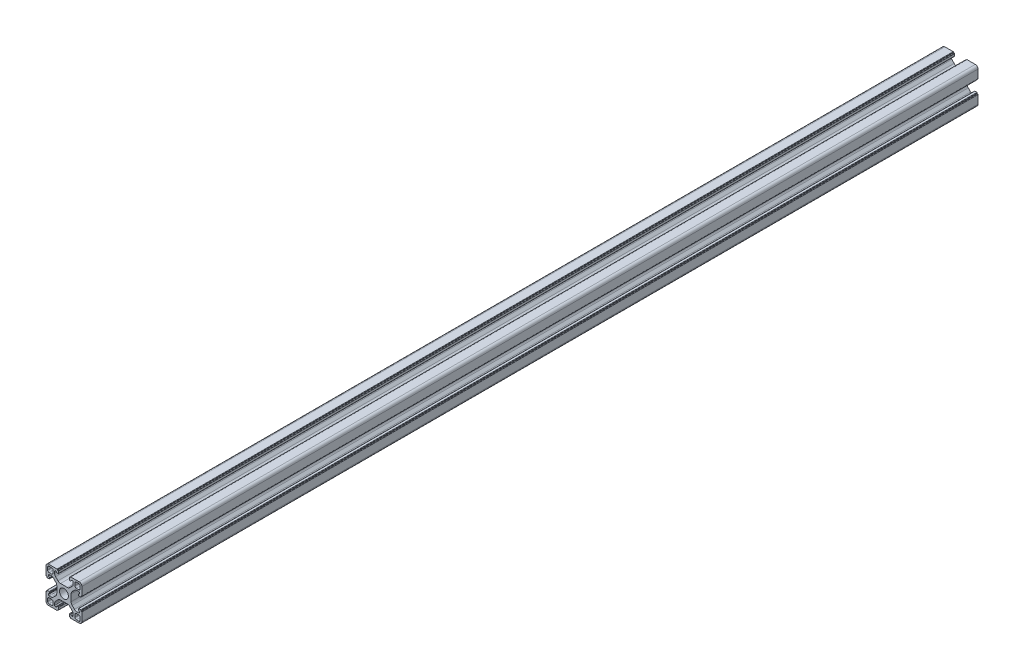
SolidWorks part; units mm, degrees
material "1060 Сплав"
ref_plane "Спереди" through (0, 0, 0) normal (0, 0, 1) x (1, 0, 0)
ref_plane "Сверху" through (0, 0, 0) normal (0, 1, 0) x (1, 0, 0)
ref_plane "Справа" through (0, 0, 0) normal (1, 0, 0) x (0, 0, -1)
sketch "Эскиз1" plane through (0, 0, 0) normal (0, 0, 1) x (1, 0, 0)
  line L0 (-22.0052, 70.3096) -> (-25.0052, 67.3096) construction
  line L1 (-31.1052, 65.2096) -> (-29.2064, 65.2096)
  line L2 (-31.1052, 61.2096) -> (-21.1052, 71.2096) construction
  line L3 (-23.5052, 68.8096) -> (-25.0052, 70.3096) construction
  line L4 (-27.7922, 65.7954) -> (-26.4909, 67.0967)
  line L5 (-24.2052, 67.3096) -> (-22.8052, 67.3096)
  line L6 (-25.0052, 68.1096) -> (-25.0052, 69.5096)
  line L7 (-22.8052, 70.3096) -> (-24.2052, 70.3096)
  line L8 (-25.9052, 69.4096) -> (-25.9052, 68.5109)
  line L9 (-27.3419, 69.2829) -> (-26.8616, 69.7632)
  line L10 (-27.9052, 70.7587) -> (-27.4052, 70.7587)
  line L11 (-27.5187, 69.2096) -> (-27.8052, 69.2096)
  line L12 (-26.508, 69.9096) -> (-26.4052, 69.9096)
  line L13 (-27.4052, 71.0596) -> (-27.4052, 70.7587)
  line L14 (-28.0552, 70.6087) -> (-28.0552, 69.4596)
  line L15 (-22.6052, 71.2096) -> (-27.2552, 71.2096)
  line L16 (-22.0052, 69.5096) -> (-22.0052, 68.1096)
  line L17 (-21.1052, 69.7096) -> (-21.1052, 65.0596)
  line L18 (-21.7061, 64.2596) -> (-22.8552, 64.2596)
  line L19 (-21.2552, 64.9096) -> (-21.5561, 64.9096)
  line L20 (-22.4052, 65.8068) -> (-22.4052, 65.9096)
  line L21 (-23.1052, 64.7961) -> (-23.1052, 64.5096)
  line L22 (-21.5561, 64.4096) -> (-21.5561, 64.9096)
  line L23 (-23.0319, 64.9729) -> (-22.5516, 65.4532)
  line L24 (-22.9052, 66.4096) -> (-23.8039, 66.4096)
  line L25 (-26.5194, 64.5226) -> (-25.2181, 65.8239)
  line L26 (-27.1052, 61.2096) -> (-27.1052, 63.1084)
  line L27 (-27.1052, 61.2096) -> (-27.1052, 59.3109)
  line L28 (-26.5194, 57.8967) -> (-25.2181, 56.5954)
  line L29 (-25.0052, 54.3096) -> (-25.0052, 52.9096)
  line L30 (-24.2052, 55.1096) -> (-22.8052, 55.1096)
  line L31 (-22.0052, 52.9096) -> (-22.0052, 54.3096)
  line L32 (-22.9052, 56.0096) -> (-23.8039, 56.0096)
  line L33 (-23.0319, 57.4464) -> (-22.5516, 56.9661)
  line L34 (-21.5561, 58.0096) -> (-21.5561, 57.5096)
  line L35 (-23.1052, 57.6232) -> (-23.1052, 57.9096)
  line L36 (-22.4052, 56.6125) -> (-22.4052, 56.5096)
  line L37 (-21.2552, 57.5096) -> (-21.5561, 57.5096)
  line L38 (-21.7061, 58.1596) -> (-22.8552, 58.1596)
  line L39 (-21.1052, 52.7096) -> (-21.1052, 57.3596)
  line L40 (-22.8052, 52.1096) -> (-24.2052, 52.1096)
  line L41 (-22.6052, 51.2096) -> (-27.2552, 51.2096)
  line L42 (-28.0552, 51.8106) -> (-28.0552, 52.9596)
  line L43 (-27.4052, 51.3596) -> (-27.4052, 51.6606)
  line L44 (-26.508, 52.5096) -> (-26.4052, 52.5096)
  line L45 (-27.5187, 53.2096) -> (-27.8052, 53.2096)
  line L46 (-27.9052, 51.6606) -> (-27.4052, 51.6606)
  line L47 (-27.3419, 53.1364) -> (-26.8616, 52.6561)
  line L48 (-25.9052, 53.0096) -> (-25.9052, 53.9084)
  line L49 (-27.7922, 56.6239) -> (-26.4909, 55.3226)
  line L50 (-31.1052, 57.2096) -> (-29.2064, 57.2096)
  line L51 (-22.0052, 52.1096) -> (-25.0052, 55.1096) construction
  line L52 (-31.1052, 61.2096) -> (-21.1052, 51.2096) construction
  line L53 (-23.5052, 53.6096) -> (-22.0052, 55.1096) construction
  line L54 (-31.1052, 57.2096) -> (-33.0039, 57.2096)
  line L55 (-34.4181, 56.6239) -> (-35.7194, 55.3226)
  line L56 (-38.0052, 55.1096) -> (-39.4052, 55.1096)
  line L57 (-37.2052, 54.3096) -> (-37.2052, 52.9096)
  line L58 (-39.4052, 52.1096) -> (-38.0052, 52.1096)
  line L59 (-36.3052, 53.0096) -> (-36.3052, 53.9084)
  line L60 (-34.8684, 53.1364) -> (-35.3487, 52.6561)
  line L61 (-34.3052, 51.6606) -> (-34.8052, 51.6606)
  line L62 (-34.6916, 53.2096) -> (-34.4052, 53.2096)
  line L63 (-35.7023, 52.5096) -> (-35.8052, 52.5096)
  line L64 (-34.8052, 51.3596) -> (-34.8052, 51.6606)
  line L65 (-34.1552, 51.8106) -> (-34.1552, 52.9596)
  line L66 (-39.6052, 51.2096) -> (-34.9552, 51.2096)
  line L67 (-40.2052, 52.9096) -> (-40.2052, 54.3096)
  line L68 (-41.1052, 52.7096) -> (-41.1052, 57.3596)
  line L69 (-40.5042, 58.1596) -> (-39.3552, 58.1596)
  line L70 (-40.9552, 57.5096) -> (-40.6542, 57.5096)
  line L71 (-39.8052, 56.6125) -> (-39.8052, 56.5096)
  line L72 (-39.1052, 57.6232) -> (-39.1052, 57.9096)
  line L73 (-40.6542, 58.0096) -> (-40.6542, 57.5096)
  line L74 (-39.1784, 57.4464) -> (-39.6587, 56.9661)
  line L75 (-39.3052, 56.0096) -> (-38.4064, 56.0096)
  line L76 (-35.6909, 57.8967) -> (-36.9922, 56.5954)
  line L77 (-35.1052, 61.2096) -> (-35.1052, 59.3109)
  line L78 (-40.2052, 52.1096) -> (-37.2052, 55.1096) construction
  line L79 (-31.1052, 61.2096) -> (-41.1052, 51.2096) construction
  line L80 (-38.7052, 53.6096) -> (-37.2052, 52.1096) construction
  line L81 (-35.1052, 61.2096) -> (-35.1052, 63.1084)
  line L82 (-35.6909, 64.5226) -> (-36.9922, 65.8239)
  line L83 (-37.2052, 68.1096) -> (-37.2052, 69.5096)
  line L84 (-38.0052, 67.3096) -> (-39.4052, 67.3096)
  line L85 (-40.2052, 69.5096) -> (-40.2052, 68.1096)
  line L86 (-39.3052, 66.4096) -> (-38.4064, 66.4096)
  line L87 (-39.1784, 64.9729) -> (-39.6587, 65.4532)
  line L88 (-40.6542, 64.4096) -> (-40.6542, 64.9096)
  line L89 (-39.1052, 64.7961) -> (-39.1052, 64.5096)
  line L90 (-39.8052, 65.8068) -> (-39.8052, 65.9096)
  line L91 (-40.9552, 64.9096) -> (-40.6542, 64.9096)
  line L92 (-40.5042, 64.2596) -> (-39.3552, 64.2596)
  line L93 (-41.1052, 69.7096) -> (-41.1052, 65.0596)
  line L94 (-39.4052, 70.3096) -> (-38.0052, 70.3096)
  line L95 (-39.6052, 71.2096) -> (-34.9552, 71.2096)
  line L96 (-34.1552, 70.6087) -> (-34.1552, 69.4596)
  line L97 (-34.8052, 71.0596) -> (-34.8052, 70.7587)
  line L98 (-35.7023, 69.9096) -> (-35.8052, 69.9096)
  line L99 (-34.6916, 69.2096) -> (-34.4052, 69.2096)
  line L100 (-34.3052, 70.7587) -> (-34.8052, 70.7587)
  line L101 (-34.8684, 69.2829) -> (-35.3487, 69.7632)
  line L102 (-36.3052, 69.4096) -> (-36.3052, 68.5109)
  line L103 (-34.4181, 65.7954) -> (-35.7194, 67.0967)
  line L104 (-31.1052, 65.2096) -> (-33.0039, 65.2096)
  line L105 (-42.8692, 61.2096) -> (-19.6008, 61.2096) construction
  line L106 (-40.2052, 70.3096) -> (-37.2052, 67.3096) construction
  line L107 (-31.1052, 49.1232) -> (-31.1052, 71.9286) construction
  line L108 (-31.1052, 61.2096) -> (-41.1052, 71.2096) construction
  line L109 (-38.7052, 68.8096) -> (-40.2052, 67.3096) construction
  arc A0 (-22.0052, 69.5096) -> (-22.8052, 70.3096) centre (-22.8052, 69.5096) ccw
  arc A1 (-24.2052, 70.3096) -> (-25.0052, 69.5096) centre (-24.2052, 69.5096) ccw
  arc A2 (-24.2052, 67.3096) -> (-25.0052, 68.1096) centre (-24.2052, 68.1096) cw
  arc A3 (-22.6052, 71.2096) -> (-21.1052, 69.7096) centre (-22.6052, 69.7096) cw
  arc A4 (-27.9052, 70.7587) -> (-28.0552, 70.6087) centre (-27.9052, 70.6087) ccw
  arc A5 (-27.2552, 71.2096) -> (-27.4052, 71.0596) centre (-27.2552, 71.0596) ccw
  arc A6 (-27.5187, 69.2096) -> (-27.3419, 69.2829) centre (-27.5187, 69.4596) ccw
  arc A7 (-27.8052, 69.2096) -> (-28.0552, 69.4596) centre (-27.8052, 69.4596) cw
  arc A8 (-26.8616, 69.7632) -> (-26.508, 69.9096) centre (-26.508, 69.4096) cw
  arc A9 (-26.4052, 69.9096) -> (-25.9052, 69.4096) centre (-26.4052, 69.4096) cw
  arc A10 (-28.6052, 61.2096) -> (-31.1052, 63.7096) centre (-31.1052, 61.2096) ccw
  arc A11 (-29.2064, 65.2096) -> (-27.7922, 65.7954) centre (-29.2064, 67.2096) ccw
  arc A12 (-25.9052, 68.5109) -> (-26.4909, 67.0967) centre (-27.9052, 68.5109) cw
  arc A13 (-22.0052, 68.1096) -> (-22.8052, 67.3096) centre (-22.8052, 68.1096) cw
  arc A14 (-22.4052, 65.9096) -> (-22.9052, 66.4096) centre (-22.9052, 65.9096) ccw
  arc A15 (-22.5516, 65.4532) -> (-22.4052, 65.8068) centre (-22.9052, 65.8068) ccw
  arc A16 (-23.1052, 64.5096) -> (-22.8552, 64.2596) centre (-22.8552, 64.5096) ccw
  arc A17 (-23.1052, 64.7961) -> (-23.0319, 64.9729) centre (-22.8552, 64.7961) cw
  arc A18 (-21.1052, 65.0596) -> (-21.2552, 64.9096) centre (-21.2552, 65.0596) cw
  arc A19 (-21.5561, 64.4096) -> (-21.7061, 64.2596) centre (-21.7061, 64.4096) cw
  arc A20 (-23.8039, 66.4096) -> (-25.2181, 65.8239) centre (-23.8039, 64.4096) ccw
  arc A21 (-27.1052, 63.1084) -> (-26.5194, 64.5226) centre (-25.1052, 63.1084) cw
  arc A22 (-22.8052, 52.1096) -> (-22.0052, 52.9096) centre (-22.8052, 52.9096) ccw
  arc A23 (-22.0052, 54.3096) -> (-22.8052, 55.1096) centre (-22.8052, 54.3096) ccw
  arc A24 (-25.0052, 54.3096) -> (-24.2052, 55.1096) centre (-24.2052, 54.3096) cw
  arc A25 (-21.1052, 52.7096) -> (-22.6052, 51.2096) centre (-22.6052, 52.7096) cw
  arc A26 (-21.5561, 58.0096) -> (-21.7061, 58.1596) centre (-21.7061, 58.0096) ccw
  arc A27 (-21.1052, 57.3596) -> (-21.2552, 57.5096) centre (-21.2552, 57.3596) ccw
  arc A28 (-23.1052, 57.6232) -> (-23.0319, 57.4464) centre (-22.8552, 57.6232) ccw
  arc A29 (-23.1052, 57.9096) -> (-22.8552, 58.1596) centre (-22.8552, 57.9096) cw
  arc A30 (-22.5516, 56.9661) -> (-22.4052, 56.6125) centre (-22.9052, 56.6125) cw
  arc A31 (-22.4052, 56.5096) -> (-22.9052, 56.0096) centre (-22.9052, 56.5096) cw
  arc A32 (-31.1052, 58.7096) -> (-28.6052, 61.2096) centre (-31.1052, 61.2096) ccw
  arc A33 (-27.1052, 59.3109) -> (-26.5194, 57.8967) centre (-25.1052, 59.3109) ccw
  arc A34 (-23.8039, 56.0096) -> (-25.2181, 56.5954) centre (-23.8039, 58.0096) cw
  arc A35 (-24.2052, 52.1096) -> (-25.0052, 52.9096) centre (-24.2052, 52.9096) cw
  arc A36 (-26.4052, 52.5096) -> (-25.9052, 53.0096) centre (-26.4052, 53.0096) ccw
  arc A37 (-26.8616, 52.6561) -> (-26.508, 52.5096) centre (-26.508, 53.0096) ccw
  arc A38 (-27.8052, 53.2096) -> (-28.0552, 52.9596) centre (-27.8052, 52.9596) ccw
  arc A39 (-27.5187, 53.2096) -> (-27.3419, 53.1364) centre (-27.5187, 52.9596) cw
  arc A40 (-27.2552, 51.2096) -> (-27.4052, 51.3596) centre (-27.2552, 51.3596) cw
  arc A41 (-27.9052, 51.6606) -> (-28.0552, 51.8106) centre (-27.9052, 51.8106) cw
  arc A42 (-25.9052, 53.9084) -> (-26.4909, 55.3226) centre (-27.9052, 53.9084) ccw
  arc A43 (-29.2064, 57.2096) -> (-27.7922, 56.6239) centre (-29.2064, 55.2096) cw
  arc A44 (-40.2052, 52.9096) -> (-39.4052, 52.1096) centre (-39.4052, 52.9096) ccw
  arc A45 (-38.0052, 52.1096) -> (-37.2052, 52.9096) centre (-38.0052, 52.9096) ccw
  arc A46 (-38.0052, 55.1096) -> (-37.2052, 54.3096) centre (-38.0052, 54.3096) cw
  arc A47 (-39.6052, 51.2096) -> (-41.1052, 52.7096) centre (-39.6052, 52.7096) cw
  arc A48 (-34.3052, 51.6606) -> (-34.1552, 51.8106) centre (-34.3052, 51.8106) ccw
  arc A49 (-34.9552, 51.2096) -> (-34.8052, 51.3596) centre (-34.9552, 51.3596) ccw
  arc A50 (-34.6916, 53.2096) -> (-34.8684, 53.1364) centre (-34.6916, 52.9596) ccw
  arc A51 (-34.4052, 53.2096) -> (-34.1552, 52.9596) centre (-34.4052, 52.9596) cw
  arc A52 (-35.3487, 52.6561) -> (-35.7023, 52.5096) centre (-35.7023, 53.0096) cw
  arc A53 (-35.8052, 52.5096) -> (-36.3052, 53.0096) centre (-35.8052, 53.0096) cw
  arc A54 (-33.6052, 61.2096) -> (-31.1052, 58.7096) centre (-31.1052, 61.2096) ccw
  arc A55 (-33.0039, 57.2096) -> (-34.4181, 56.6239) centre (-33.0039, 55.2096) ccw
  arc A56 (-36.3052, 53.9084) -> (-35.7194, 55.3226) centre (-34.3052, 53.9084) cw
  arc A57 (-40.2052, 54.3096) -> (-39.4052, 55.1096) centre (-39.4052, 54.3096) cw
  arc A58 (-39.8052, 56.5096) -> (-39.3052, 56.0096) centre (-39.3052, 56.5096) ccw
  arc A59 (-39.6587, 56.9661) -> (-39.8052, 56.6125) centre (-39.3052, 56.6125) ccw
  arc A60 (-39.1052, 57.9096) -> (-39.3552, 58.1596) centre (-39.3552, 57.9096) ccw
  arc A61 (-39.1052, 57.6232) -> (-39.1784, 57.4464) centre (-39.3552, 57.6232) cw
  arc A62 (-41.1052, 57.3596) -> (-40.9552, 57.5096) centre (-40.9552, 57.3596) cw
  arc A63 (-40.6542, 58.0096) -> (-40.5042, 58.1596) centre (-40.5042, 58.0096) cw
  arc A64 (-38.4064, 56.0096) -> (-36.9922, 56.5954) centre (-38.4064, 58.0096) ccw
  arc A65 (-35.1052, 59.3109) -> (-35.6909, 57.8967) centre (-37.1052, 59.3109) cw
  arc A66 (-39.4052, 70.3096) -> (-40.2052, 69.5096) centre (-39.4052, 69.5096) ccw
  arc A67 (-40.2052, 68.1096) -> (-39.4052, 67.3096) centre (-39.4052, 68.1096) ccw
  arc A68 (-37.2052, 68.1096) -> (-38.0052, 67.3096) centre (-38.0052, 68.1096) cw
  arc A69 (-41.1052, 69.7096) -> (-39.6052, 71.2096) centre (-39.6052, 69.7096) cw
  arc A70 (-40.6542, 64.4096) -> (-40.5042, 64.2596) centre (-40.5042, 64.4096) ccw
  arc A71 (-41.1052, 65.0596) -> (-40.9552, 64.9096) centre (-40.9552, 65.0596) ccw
  arc A72 (-39.1052, 64.7961) -> (-39.1784, 64.9729) centre (-39.3552, 64.7961) ccw
  arc A73 (-39.1052, 64.5096) -> (-39.3552, 64.2596) centre (-39.3552, 64.5096) cw
  arc A74 (-39.6587, 65.4532) -> (-39.8052, 65.8068) centre (-39.3052, 65.8068) cw
  arc A75 (-39.8052, 65.9096) -> (-39.3052, 66.4096) centre (-39.3052, 65.9096) cw
  arc A76 (-31.1052, 63.7096) -> (-33.6052, 61.2096) centre (-31.1052, 61.2096) ccw
  arc A77 (-35.1052, 63.1084) -> (-35.6909, 64.5226) centre (-37.1052, 63.1084) ccw
  arc A78 (-38.4064, 66.4096) -> (-36.9922, 65.8239) centre (-38.4064, 64.4096) cw
  arc A79 (-38.0052, 70.3096) -> (-37.2052, 69.5096) centre (-38.0052, 69.5096) cw
  arc A80 (-35.8052, 69.9096) -> (-36.3052, 69.4096) centre (-35.8052, 69.4096) ccw
  arc A81 (-35.3487, 69.7632) -> (-35.7023, 69.9096) centre (-35.7023, 69.4096) ccw
  arc A82 (-34.4052, 69.2096) -> (-34.1552, 69.4596) centre (-34.4052, 69.4596) ccw
  arc A83 (-34.6916, 69.2096) -> (-34.8684, 69.2829) centre (-34.6916, 69.4596) cw
  arc A84 (-34.9552, 71.2096) -> (-34.8052, 71.0596) centre (-34.9552, 71.0596) cw
  arc A85 (-34.3052, 70.7587) -> (-34.1552, 70.6087) centre (-34.3052, 70.6087) cw
  arc A86 (-36.3052, 68.5109) -> (-35.7194, 67.0967) centre (-34.3052, 68.5109) ccw
  arc A87 (-33.0039, 65.2096) -> (-34.4181, 65.7954) centre (-33.0039, 67.2096) cw
  point P0 (-31.1052, 61.2096)
  point P9 (-31.1052, 61.2096)
  point P40 (-22.4052, 64.9096)
  point P93 (-27.4052, 52.5096)
  point P144 (-27.4052, 69.9096)
  point P152 (-22.4052, 57.5096)
  point P153 (-31.1052, 57.2854)
  point P154 (-31.1052, 61.2096)
  point P189 (-39.8052, 57.5096)
  point P228 (-34.8052, 52.5096)
  point P229 (-35.0294, 61.2096)
  point P230 (-31.1052, 61.2096)
  point P268 (-34.8052, 69.9096)
  point P273 (-27.1809, 61.2096)
  point P306 (-39.8052, 64.9096)
  point P307 (-31.1052, 65.1339)
  point P309 (-31.1052, 61.2096)
  dimension "D3" = 5
  dimension "D6" = 2
  dimension "D1" = 2
  dimension "D2" = 6
  dimension "D4" = 4
  dimension "D5" = 0.9
extrude "Бобышка-Вытянуть1" add sketch "Эскиз1" along normal blind 500
